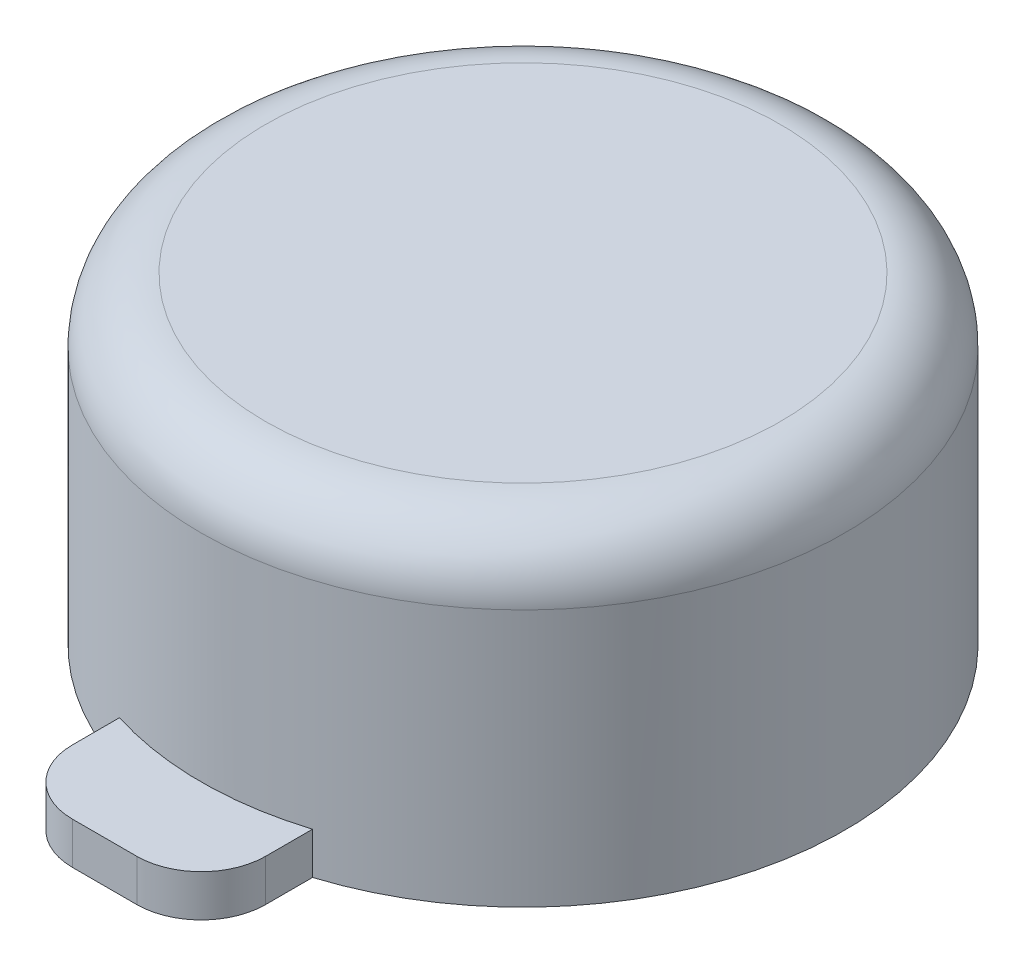
SolidWorks part; units mm, degrees
ref_plane "Front Plane" through (0, 0, 0) normal (0, 0, 1) x (1, 0, 0)
ref_plane "Top Plane" through (0, 0, 0) normal (0, 1, 0) x (1, 0, 0)
ref_plane "Right Plane" through (0, 0, 0) normal (1, 0, 0) x (0, 0, -1)
sketch "Sketch1" plane through (0, 0, 0) normal (0, 1, 0) x (1, 0, 0)
  circle A0 centre (0, 0) radius 12.7
  dimension "D1" = 25.4
extrude "Boss-Extrude1" add sketch "Sketch1" along normal blind 12.7 contours A0
fillet "Fillet1" radius 2.54 1 edges at (0, 12.7, 12.7)
shell "Shell1" thickness 1.27
ref_plane "Plane1" through (0, 0, 16.51) normal (0, 0, 1) x (1, 0, 0)
sketch "Sketch4" plane through (0, 0, 16.51) normal (0, 0, 1) x (1, 0, 0)
  line L0 (-12.7, 0) -> (12.7, 0) construction
  line L1 (-3.81, 0) -> (3.81, 0)
  line L2 (-3.81, 0) -> (-3.81, 1.651)
  line L3 (-3.81, 1.651) -> (3.81, 1.651)
  line L4 (3.81, 0) -> (3.81, 1.651)
  dimension "D1" = 1.651
  dimension "D2" = 7.62
  dimension "D3" = 3.81
extrude "Boss-Extrude2" add sketch "Sketch4" against normal up to surface (4.395 mm away)
fillet "Fillet2" radius 2.54 2 edges at (-3.81, 0.8255, 16.51) (3.81, 0.8255, 16.51)
